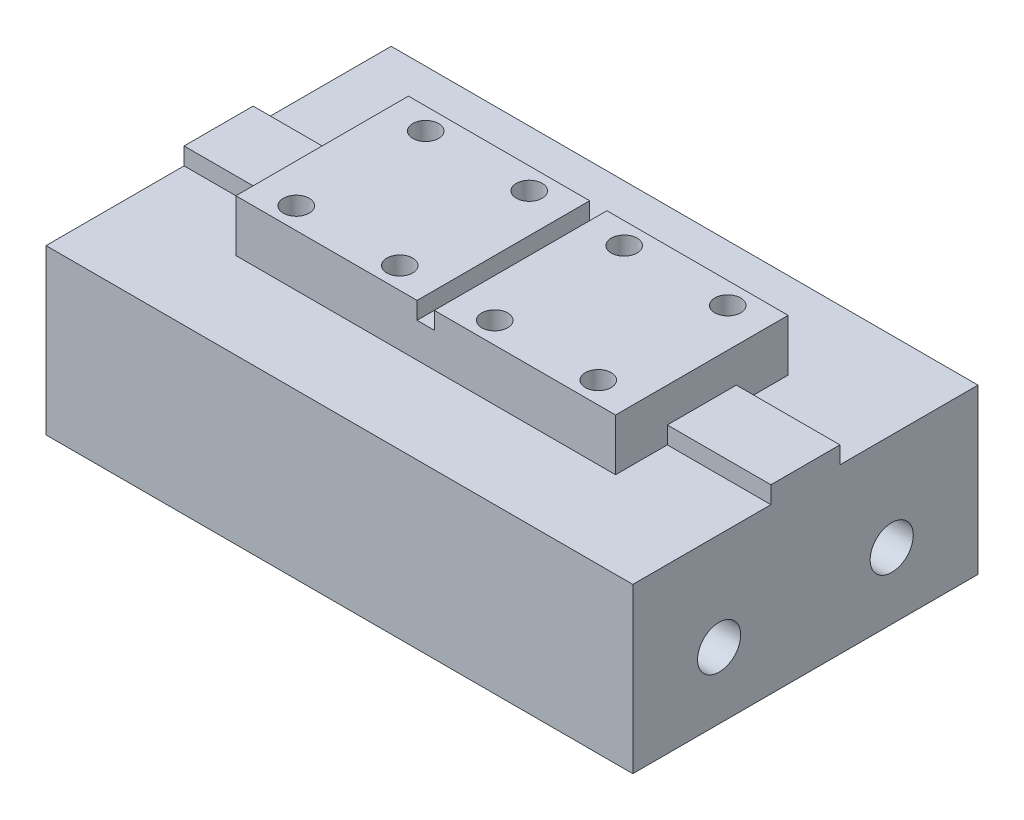
SolidWorks part; units mm, degrees
ref_plane "前视基准面" through (0, 0, 0) normal (0, 0, 1) x (1, 0, 0)
ref_plane "上视基准面" through (0, 0, 0) normal (0, 1, 0) x (1, 0, 0)
ref_plane "右视基准面" through (0, 0, 0) normal (1, 0, 0) x (0, 0, -1)
sketch "草图1" plane through (0, 0, 0) normal (0, 1, 0) x (1, 0, 0)
  line L0 (-34, -20) -> (34, -20)
  line L1 (-34, -20) -> (-34, 20)
  line L2 (34, -20) -> (34, 20)
  line L3 (-34, 20) -> (34, 20)
  line L4 (-34, -20) -> (34, 20) construction
  line L5 (34, -20) -> (-34, 20) construction
  point P1 (0, 0)
  dimension "D1" = 40
  dimension "D2" = 68
extrude "凸台-拉伸1" add sketch "草图1" along normal blind 19
sketch "草图2" plane through (0, 19, 0) normal (0, 1, 0) x (1, 0, 0)
  line L0 (-22, -10) -> (22, -10)
  line L1 (-22, -10) -> (-22, 10)
  line L2 (22, -10) -> (22, 10)
  line L3 (-22, 10) -> (22, 10)
  line L4 (-22, -10) -> (22, 10) construction
  line L5 (22, -10) -> (-22, 10) construction
  line L6 (-34, 20) -> (-34, -20) construction
  point P1 (0, 0)
  dimension "D1" = 20
  dimension "D2" = 44
extrude "凸台-拉伸2" add sketch "草图2" along normal blind 6
sketch "草图4" plane through (0, 25, 0) normal (0, 1, 0) x (1, 0, 0)
  line L0 (-1, -10) -> (1, -10)
  line L1 (-1, -10) -> (-1, 10)
  line L2 (1, -10) -> (1, 10)
  line L3 (-1, 10) -> (1, 10)
  line L4 (-1, -10) -> (1, 10) construction
  line L5 (1, -10) -> (-1, 10) construction
  point P1 (0, 0)
  dimension "D1" = 2
  dimension "D2" = 20
extrude "切除-拉伸1" cut sketch "草图4" against normal blind 2
sketch "草图5" plane through (0, 19, 0) normal (0, 1, 0) x (1, 0, 0)
  line L0 (-34, -4) -> (34, -4)
  line L1 (-34, -4) -> (-34, 4)
  line L2 (34, -4) -> (34, 4)
  line L3 (-34, 4) -> (34, 4)
  line L4 (-34, -4) -> (34, 4) construction
  line L5 (34, -4) -> (-34, 4) construction
  point P1 (0, 0)
  dimension "D1" = 8
  dimension "D2" = 68
extrude "凸台-拉伸3" add sketch "草图5" along normal blind 2
sketch "草图6" plane through (0, 25, 0) normal (0, 1, 0) x (1, 0, 0)
  line L0 (11.5, -10) -> (11.5, 0)
  line L1 (1, -10) -> (22, -10) construction
  line L2 (17.5, -7.5) -> (5.5, -7.5)
  line L3 (17.5, -7.5) -> (17.5, 7.5)
  line L4 (5.5, -7.5) -> (5.5, 7.5)
  line L5 (17.5, 7.5) -> (5.5, 7.5)
  line L6 (17.5, -7.5) -> (5.5, 7.5) construction
  line L7 (5.5, -7.5) -> (17.5, 7.5) construction
  dimension "D1" = 15
  dimension "D2" = 12
hole_wizard "大小mm 暗销孔1" positions "3D草图1" profile "草图7" hole size "Ø3.0" standard "ANSI Metric"
sketch3d "3D草图1"
  point P0 (17.5, 25, -7.5)
  point P3 (17.5, 25, 7.5)
  point P6 (5.5, 25, 7.5)
  point P9 (5.5, 25, -7.5)
sketch "草图7" plane through (17.5, 25, -7.5) normal (1, 0, 0) x (0, 0, 1)
  line L0 (0, 0) -> (0, 4.9013)
  line L1 (0, 4.9013) -> (1.5, 4)
  line L2 (1.5, 4) -> (1.5, 0)
  line L5 (1.5, 0) -> (0, 0)
  line L10 (0, 4.9013) -> (-1.5, 4) construction
  line L11 (0, -6.35) -> (0, 107.95) construction
  dimension "孔直径" = 3
  dimension "孔深度" = 4
  dimension "导头角度" = 118
ref_plane "基准面2" through (0, 0, 0) normal (1, 0, 0) x (0, 0, -1)
mirror "镜向1" about plane through (0, 0, 0) normal (1, 0, 0) of "大小mm 暗销孔1"
sketch "草图8" plane through (0, 0, 0) normal (0, -1, 0) x (1, 0, 0)
  line L0 (0, 0) -> (-21, 0)
  line L1 (0, 0) -> (21, 0)
  dimension "D1" = 21
  dimension "D2" = 21
hole_wizard "大小mm 暗销孔2" positions "3D草图2" profile "草图9" hole size "Ø4.0" standard "ANSI Metric"
sketch3d "3D草图2"
  point P0 (21, 0, 0)
  point P3 (-21, 0, 0)
sketch "草图9" plane through (21, 0, 0) normal (1, 0, 0) x (0, 0, -1)
  line L0 (0, 0) -> (0, 11.2017)
  line L1 (0, 11.2017) -> (2, 10)
  line L2 (2, 10) -> (2, 0)
  line L5 (2, 0) -> (0, 0)
  line L10 (0, 11.2017) -> (-2, 10) construction
  line L11 (0, -6.35) -> (0, 107.95) construction
  dimension "孔直径" = 4
  dimension "孔深度" = 10
  dimension "导头角度" = 118
sketch "草图10" plane through (34, 0, 0) normal (1, 0, 0) x (0, 0, -1)
  line L0 (0, 0) -> (10, 0)
  line L1 (-20, 0) -> (20, 0) construction
  line L2 (10, 0) -> (10, 7.7)
  line L3 (10, 7.7) -> (-10, 7.7)
  line L4 (-10, 7.7) -> (-10, 0)
  dimension "D1" = 7.7
  dimension "D2" = 20
  dimension "D3" = 10
hole_wizard "大小mm 暗销孔3" positions "3D草图3" profile "草图11" hole size "Ø5.0" standard "ANSI Metric"
sketch3d "3D草图3"
  point P0 (34, 7.7, -10)
  point P3 (34, 7.7, 10)
sketch "草图11" plane through (34, 7.7, -10) normal (0, 1, 0) x (0, 0, -1)
  line L0 (0, 0) -> (0, 6.5022)
  line L1 (0, 6.5022) -> (2.5, 5)
  line L2 (2.5, 5) -> (2.5, 0)
  line L5 (2.5, 0) -> (0, 0)
  line L10 (0, 6.5022) -> (-2.5, 5) construction
  line L11 (0, -6.35) -> (0, 107.95) construction
  dimension "孔直径" = 5
  dimension "孔深度" = 5
  dimension "导头角度" = 118
